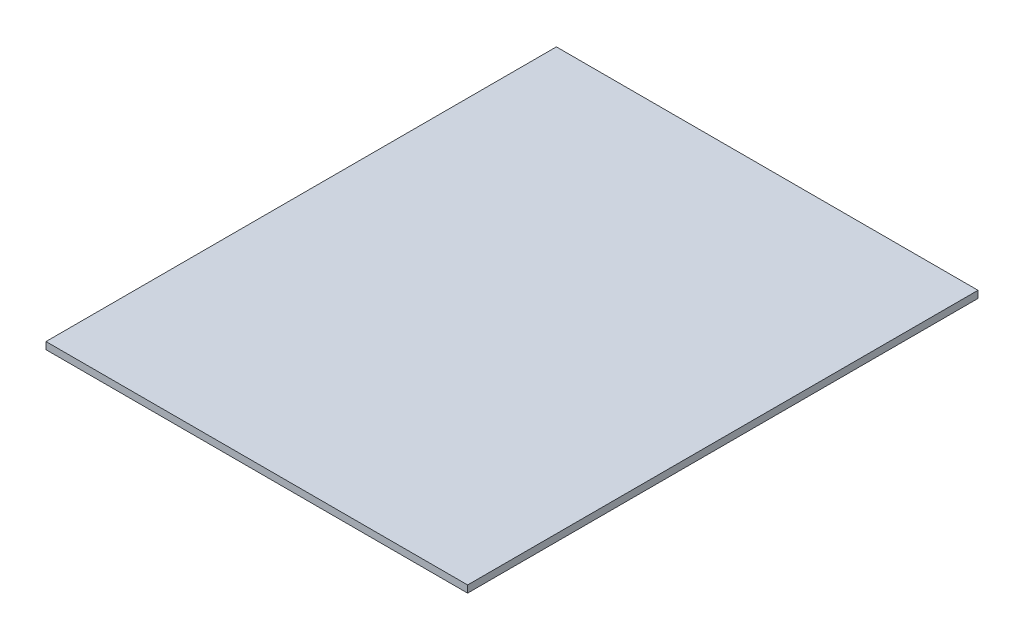
SolidWorks part; units mm, degrees
ref_plane "Front Plane" through (0, 0, 0) normal (0, 0, 1) x (1, 0, 0)
ref_plane "Top Plane" through (0, 0, 0) normal (0, 1, 0) x (1, 0, 0)
ref_plane "Right Plane" through (0, 0, 0) normal (1, 0, 0) x (0, 0, -1)
sketch "Sketch1" plane through (0, 0, 0) normal (0, 1, 0) x (1, 0, 0)
  line L1 (0, 0) -> (95, 0)
  line L2 (0, 0) -> (0, 115)
  line L3 (0, 115) -> (95, 115)
  line L4 (95, 0) -> (95, 115)
  dimension "D1" = 95
  dimension "D2" = 115
extrude "Boss-Extrude1" add sketch "Sketch1" along normal blind 1.6
